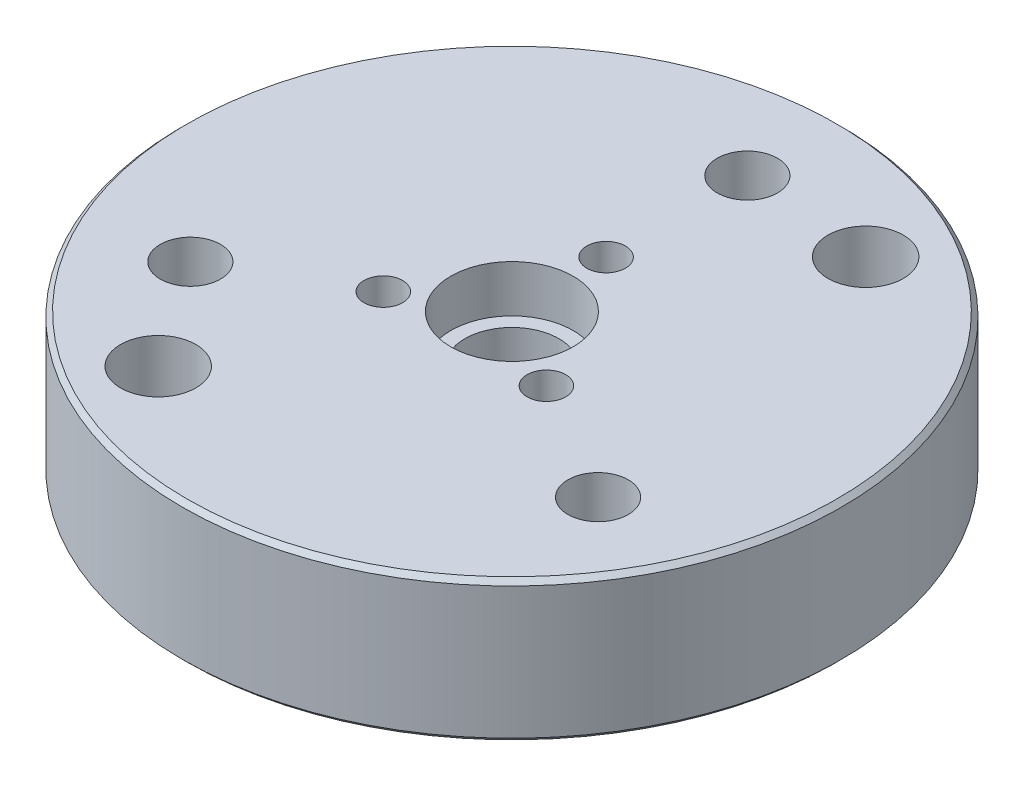
SolidWorks part; units mm, degrees
material "Plain Carbon Steel"
ref_plane "Front Plane" through (0, 0, 0) normal (0, 0, 1) x (1, 0, 0)
ref_plane "Top Plane" through (0, 0, 0) normal (0, 1, 0) x (1, 0, 0)
ref_plane "Right Plane" through (0, 0, 0) normal (1, 0, 0) x (0, 0, -1)
sketch "Sketch1" plane through (0, 0, 0) normal (0, 1, 0) x (1, 0, 0)
  circle A0 centre (0, 0) radius 35
  dimension "D1" = 70
extrude "Boss-Extrude1" add sketch "Sketch1" along normal blind 15
sketch "Sketch2" plane through (0, 15, 0) normal (0, 1, 0) x (1, 0, 0)
  circle A0 centre (0, 0) radius 5
  dimension "D1" = 10
extrude "Cut-Extrude1" cut sketch "Sketch2" against normal up to next
sketch "Sketch3" plane through (0, 15, 0) normal (0, 1, 0) x (1, 0, 0)
  circle A0 centre (0, 0) radius 6.5
  dimension "D1" = 13
extrude "Cut-Extrude2" cut sketch "Sketch3" against normal blind 5
sketch "Sketch4" plane through (0, 15, 0) normal (0, 1, 0) x (1, 0, 0)
  circle A0 centre (0, 10) radius 2.05 construction
  circle A1 centre (8.6603, -5) radius 2.05 construction
  circle A2 centre (-8.6603, -5) radius 2.05 construction
  circle A3 centre (0, 10) radius 2.05
  circle A4 centre (8.6603, -5) radius 2.05
  circle A5 centre (-8.6603, -5) radius 2.05
  circle A6 centre (0, 0) radius 10 construction
extrude "Cut-Extrude3" cut sketch "Sketch4" against normal up to next
hole_wizard "M6 Clearance Hole1" positions "Sketch11" profile "Sketch6" hole size "M6" standard "ISO" end condition through all
sketch "Sketch11" plane through (0, 0, 0) normal (0, -1, 0) x (-1, 0, 0)
  circle A0 centre (0, 0) radius 25 construction
  point P0 (0, 25)
  point P3 (21.6506, -12.5)
  point P6 (-21.6506, -12.5)
sketch "Sketch6" plane through (0, 0, -25) normal (1, 0, 0) x (0, 0, -1)
  line L0 (0, 0) -> (0, 15)
  line L1 (0, 15) -> (3.2, 15)
  line L2 (3.2, 15) -> (3.2, 0)
  line L5 (3.2, 0) -> (0, 0)
  line L11 (0, -6.35) -> (0, 107.95) construction
  dimension "Thru Hole Dia." = 6.4
  dimension "Thru Hole Depth" = 15
hole_wizard "Ø8.0mm Dowel Hole1" positions "Sketch13" profile "Sketch9" hole size "Ø8.0" standard "ISO" end condition through all
sketch "Sketch13" plane through (0, 0, 0) normal (0, -1, 0) x (-1, 0, 0)
  line L0 (0, 0) -> (-13.75, 23.8157) construction
  circle A0 centre (0, 0) radius 27.5 construction
  point P0 (-13.75, 23.8157)
  point P3 (13.75, -23.8157)
  dimension "D1" = 55
sketch "Sketch9" plane through (13.75, 0, -23.8157) normal (1, 0, 0) x (0, 0, -1)
  line L0 (0, 0) -> (0, 15)
  line L1 (0, 15) -> (4, 15)
  line L2 (4, 15) -> (4, 0)
  line L5 (4, 0) -> (0, 0)
  line L11 (0, -6.35) -> (0, 107.95) construction
  dimension "Thru Hole Dia." = 8
  dimension "Thru Hole Depth" = 15
chamfer "Chamfer1" distance 0.5 angle 45 2 edges at (0, 0, 35) (0, 15, 35)
